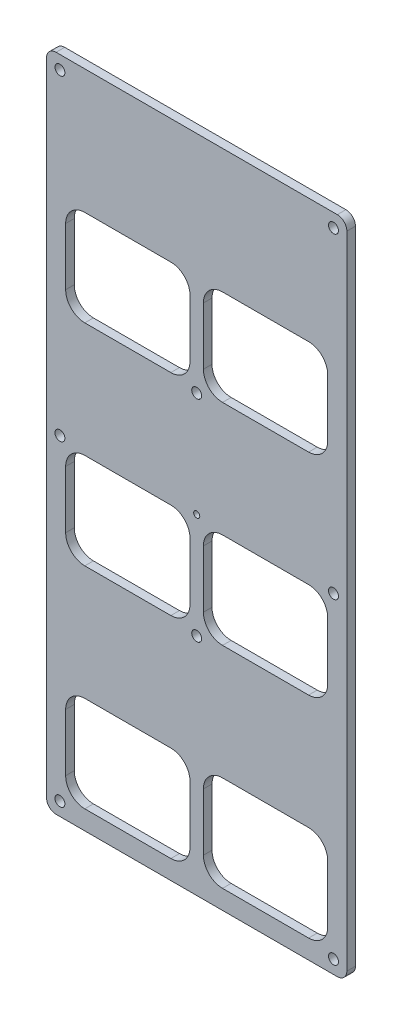
SolidWorks part; units mm, degrees
material "ABS PC"
ref_plane "前视基准面" through (0, 0, 0) normal (0, 0, 1) x (1, 0, 0)
ref_plane "上视基准面" through (0, 0, 0) normal (0, 1, 0) x (1, 0, 0)
ref_plane "右视基准面" through (0, 0, 0) normal (1, 0, 0) x (0, 0, -1)
sketch "草图1" plane through (0, 0, 0) normal (0, 0, 1) x (1, 0, 0)
  line L1 (0, 0) -> (157, 0)
  line L2 (0, 0) -> (0, 345)
  line L3 (0, 345) -> (157, 345)
  line L4 (157, 0) -> (157, 345)
  dimension "D1" = 345
  dimension "D2" = 157
extrude "凸台-拉伸1" add sketch "草图1" along normal blind 4.5
sketch "草图2" plane through (0, 0, 4.5) normal (0, 0, 1) x (1, 0, 0)
  line L0 (0, 345) -> (0, 0) construction
  line L1 (20, 60) -> (65, 60)
  line L2 (10, 50) -> (10, 20)
  line L3 (20, 10) -> (65, 10)
  line L4 (75, 50) -> (75, 20)
  line L5 (0, 0) -> (157, 0) construction
  line L34 (92, 60) -> (137, 60)
  line L35 (82, 50) -> (82, 20)
  line L36 (92, 10) -> (137, 10)
  line L37 (147, 50) -> (147, 20)
  line L38 (92, 170) -> (137, 170)
  line L39 (82, 160) -> (82, 130)
  line L40 (92, 120) -> (137, 120)
  line L41 (147, 160) -> (147, 130)
  line L42 (92, 280) -> (137, 280)
  line L43 (82, 270) -> (82, 240)
  line L44 (92, 230) -> (137, 230)
  line L45 (147, 270) -> (147, 240)
  line L46 (20, 170) -> (65, 170)
  line L47 (10, 160) -> (10, 130)
  line L48 (20, 120) -> (65, 120)
  line L49 (75, 160) -> (75, 130)
  line L50 (20, 280) -> (65, 280)
  line L51 (10, 270) -> (10, 240)
  line L52 (20, 230) -> (65, 230)
  line L53 (75, 270) -> (75, 240)
  arc A0 (10, 20) -> (20, 10) centre (20, 20) ccw
  arc A5 (65, 10) -> (75, 20) centre (65, 20) ccw
  arc A6 (20, 60) -> (10, 50) centre (20, 50) ccw
  arc A7 (65, 60) -> (75, 50) centre (65, 50) cw
  arc A24 (82, 20) -> (92, 10) centre (92, 20) ccw
  arc A25 (137, 10) -> (147, 20) centre (137, 20) ccw
  arc A26 (92, 60) -> (82, 50) centre (92, 50) ccw
  arc A27 (137, 60) -> (147, 50) centre (137, 50) cw
  arc A28 (82, 130) -> (92, 120) centre (92, 130) ccw
  arc A29 (137, 120) -> (147, 130) centre (137, 130) ccw
  arc A30 (92, 170) -> (82, 160) centre (92, 160) ccw
  arc A31 (137, 170) -> (147, 160) centre (137, 160) cw
  arc A32 (82, 240) -> (92, 230) centre (92, 240) ccw
  arc A33 (137, 230) -> (147, 240) centre (137, 240) ccw
  arc A34 (92, 280) -> (82, 270) centre (92, 270) ccw
  arc A35 (137, 280) -> (147, 270) centre (137, 270) cw
  arc A36 (10, 130) -> (20, 120) centre (20, 130) ccw
  arc A37 (65, 120) -> (75, 130) centre (65, 130) ccw
  arc A38 (20, 170) -> (10, 160) centre (20, 160) ccw
  arc A39 (65, 170) -> (75, 160) centre (65, 160) cw
  arc A40 (10, 240) -> (20, 230) centre (20, 240) ccw
  arc A41 (65, 230) -> (75, 240) centre (65, 240) ccw
  arc A42 (20, 280) -> (10, 270) centre (20, 270) ccw
  arc A43 (65, 280) -> (75, 270) centre (65, 270) cw
  point P10 (10, 10)
  point P43 (10, 60)
  point P46 (75, 60)
  dimension "D7" = 10
  dimension "D1" = 65
  dimension "D2" = 50
  dimension "D3" = 10
  dimension "D4" = 10
  dimension "D5" = 2
  dimension "D6" = 3
extrude "切除-拉伸1" cut sketch "草图2" against normal blind 4.5
sketch "草图3" plane through (0, 0, 4.5) normal (0, 0, 1) x (1, 0, 0)
  line L0 (0, 345) -> (0, 0) construction
  line L1 (7, 338) -> (150, 338) construction
  line L2 (7, 338) -> (7, 7) construction
  line L3 (7, 7) -> (150, 7) construction
  line L4 (150, 338) -> (150, 7) construction
  line L5 (157, 345) -> (0, 345) construction
  line L6 (157, 0) -> (157, 345) construction
  line L7 (0, 0) -> (157, 0) construction
  line L9 (78.5, 338) -> (78.5, 7) construction
  line L10 (20, 120) -> (65, 120) construction
  line L11 (137, 170) -> (92, 170) construction
  line L12 (92, 230) -> (137, 230) construction
  circle A0 centre (7, 338) radius 2.6
  circle A1 centre (150, 338) radius 2.6
  circle A2 centre (150, 7) radius 2.6
  circle A3 centre (7, 7) radius 2.6
  circle A4 centre (150, 172.5) radius 2.6
  circle A5 centre (7, 172.5) radius 2.6
  circle A6 centre (78.5, 172.5) radius 1.6
  circle A7 centre (78.5, 227.5) radius 2.6
  circle A8 centre (78.5, 117.5) radius 2.6
  dimension "D5" = 5.2
  dimension "D9" = 3.2
  dimension "D1" = 7
  dimension "D2" = 7
  dimension "D3" = 7
  dimension "D4" = 7
  dimension "D6" = 2.5
  dimension "D7" = 2.5
  dimension "D8" = 2.5
extrude "切除-拉伸2" cut sketch "草图3" against normal blind 4.5
fillet "圆角1" radius 5 4 edges at (157, 0, 2.25) (0, 0, 2.25) (157, 345, 2.25) (0, 345, 2.25)
